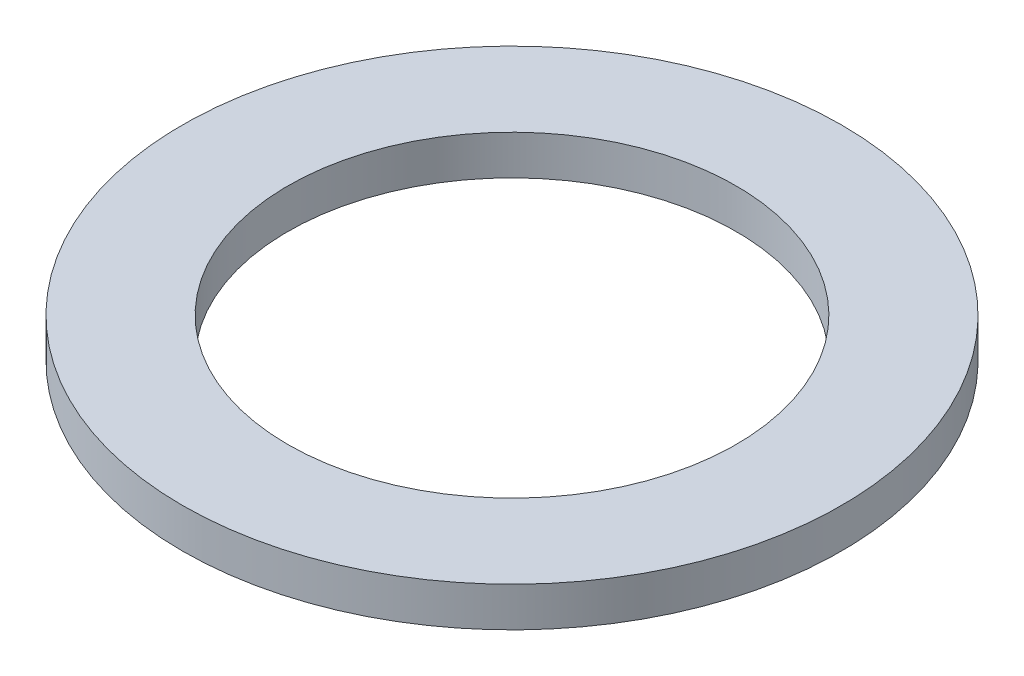
SolidWorks part; units mm, degrees
ref_plane "Płaszczyzna przednia" through (0, 0, 0) normal (0, 0, 1) x (1, 0, 0)
ref_plane "Płaszczyzna górna" through (0, 0, 0) normal (0, 1, 0) x (1, 0, 0)
ref_plane "Płaszczyzna prawa" through (0, 0, 0) normal (1, 0, 0) x (0, 0, -1)
sketch "Szkic1" plane through (0, 0, 0) normal (0, 0, 1) x (1, 0, 0)
  line L0 (17, 0) -> (25, 0)
  line L1 (25, 0) -> (25, -3)
  line L2 (25, -3) -> (17, -3)
  line L5 (17, -3) -> (17, 0)
  line L6 (0, 0) -> (0, -23.9396) construction
  point P2 (0, 0)
  dimension "D1" = 34
  dimension "D2" = 50
  dimension "D4" = 3
revolve "Obrót1" add sketch "Szkic1" angle 360 about L6
